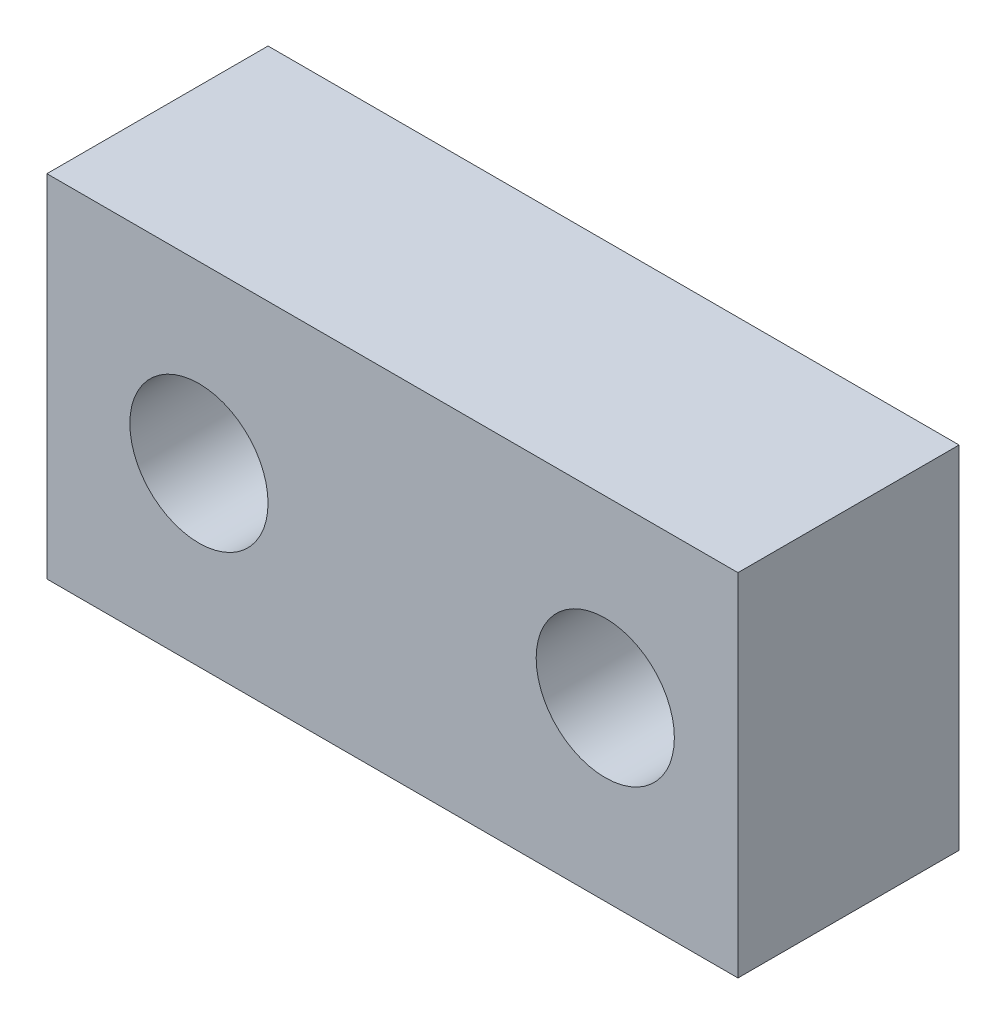
SolidWorks part; units mm, degrees
ref_plane "Plan de face" through (0, 0, 0) normal (0, 0, 1) x (1, 0, 0)
ref_plane "Plan de dessus" through (0, 0, 0) normal (0, 1, 0) x (1, 0, 0)
ref_plane "Plan de droite" through (0, 0, 0) normal (1, 0, 0) x (0, 0, -1)
sketch "Esquisse1" plane through (0, 0, 0) normal (0, 0, 1) x (1, 0, 0)
  line L1 (-12.5, 6.35) -> (12.5, 6.35)
  line L2 (-12.5, 6.35) -> (-12.5, -6.35)
  line L3 (-12.5, -6.35) -> (12.5, -6.35)
  line L4 (12.5, 6.35) -> (12.5, -6.35)
  line L5 (-12.5, 6.35) -> (12.5, -6.35) construction
  line L6 (-12.5, -6.35) -> (12.5, 6.35) construction
  point P0 (0, 0)
  dimension "D1" = 12.7
  dimension "D2" = 25
extrude "Boss.-Extru.1" add sketch "Esquisse1" along normal blind 8
sketch "Esquisse2" plane through (0, 0, 0) normal (0, 0, -1) x (-1, 0, 0)
  line L2 (12.5, -6.35) -> (-12.5, -6.35) construction
  line L3 (-12.5, -6.35) -> (-12.5, 6.35) construction
  circle A0 centre (-7.7, 0.025) radius 2.5
  circle A1 centre (7, 0.025) radius 2.5
  point P2 (0, 0)
  point P5 (0, 0)
  dimension "D1" = 5
  dimension "D2" = 5
  dimension "D3" = 6.375
  dimension "D4" = 4.8
  dimension "D5" = 14.7
extrude "Enlèv. mat.-Extru.1" cut sketch "Esquisse2" against normal blind 10
